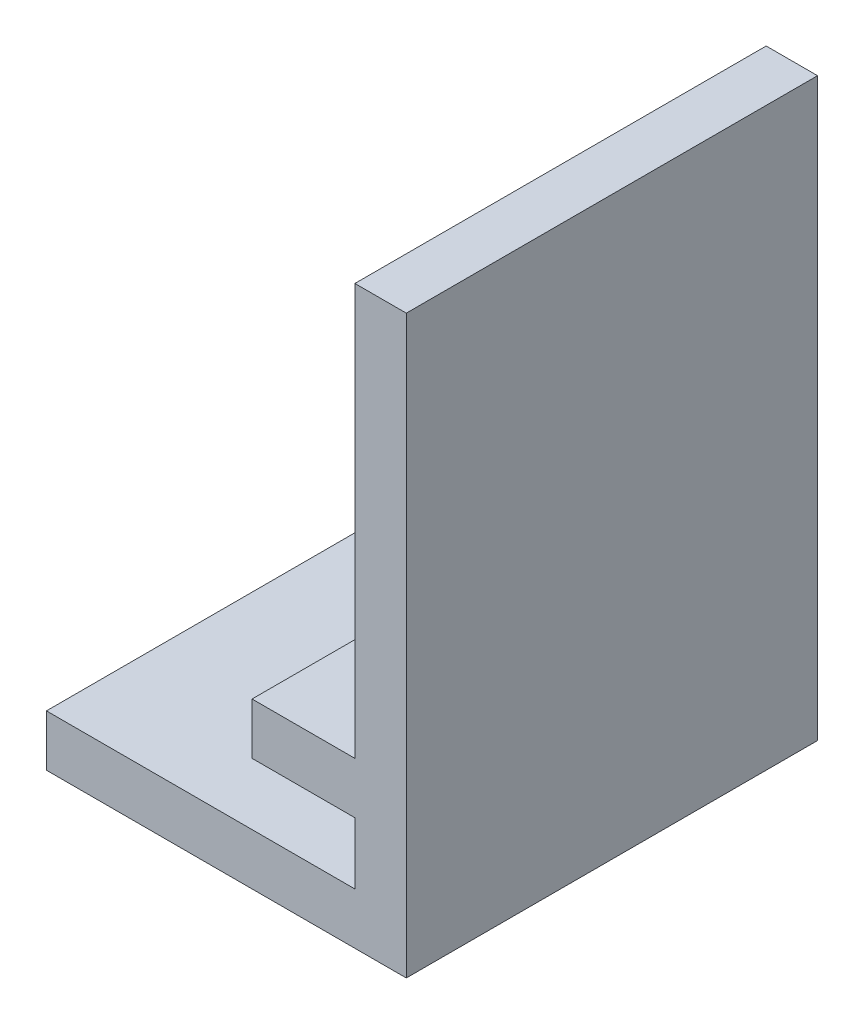
SolidWorks part; units mm, degrees
ref_plane "Front Plane" through (0, 0, 0) normal (0, 0, 1) x (1, 0, 0)
ref_plane "Top Plane" through (0, 0, 0) normal (0, 1, 0) x (1, 0, 0)
ref_plane "Right Plane" through (0, 0, 0) normal (1, 0, 0) x (0, 0, -1)
sketch "Sketch1" plane through (0, 0, 0) normal (0, 0, 1) x (1, 0, 0)
  line L0 (0, 0) -> (0, 35.56)
  line L1 (0, 35.56) -> (-3.175, 35.56)
  line L2 (-3.175, 35.56) -> (-3.175, 10.16)
  line L3 (-3.175, 10.16) -> (-9.525, 10.16)
  line L4 (-9.525, 10.16) -> (-9.525, 6.985)
  line L5 (-9.525, 6.985) -> (-3.175, 6.985)
  line L6 (-3.175, 6.985) -> (-3.175, 3.175)
  line L7 (-3.175, 3.175) -> (-22.225, 3.175)
  line L8 (-22.225, 3.175) -> (-22.225, 0)
  line L9 (-22.225, 0) -> (0, 0)
  dimension "D1" = 3.81
  dimension "D2" = 25.4
  dimension "D3" = 3.175
  dimension "D4" = 3.175
  dimension "D5" = 3.175
  dimension "D6" = 19.05
  dimension "D7" = 6.35
extrude "Boss-Extrude1" add sketch "Sketch1" along normal blind 25.4
